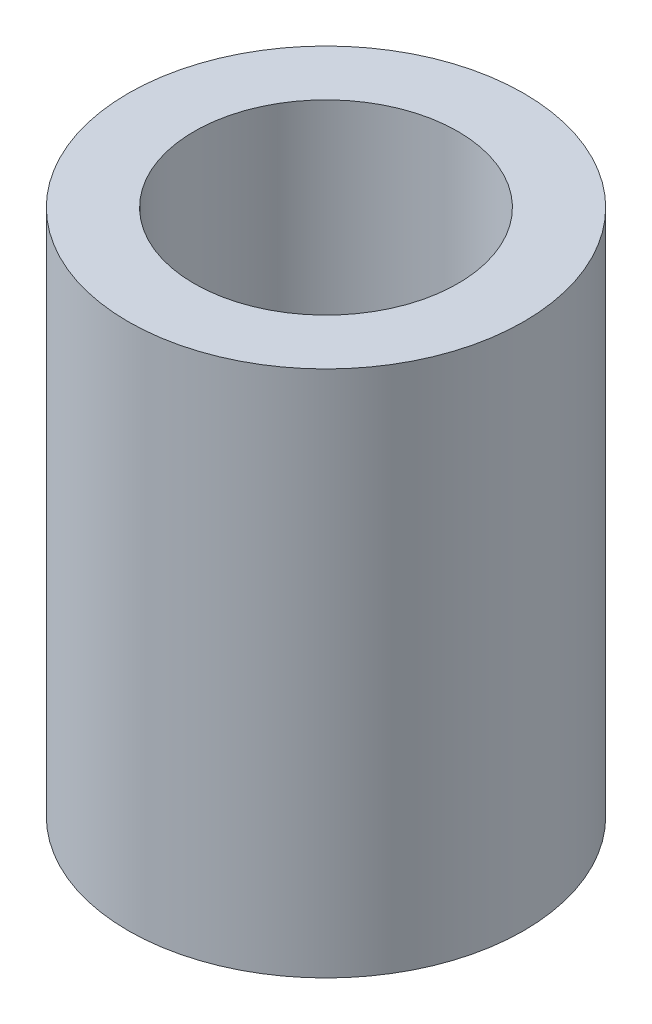
SolidWorks part; units mm, degrees
ref_plane "Front Plane" through (0, 0, 0) normal (0, 0, 1) x (1, 0, 0)
ref_plane "Top Plane" through (0, 0, 0) normal (0, 1, 0) x (1, 0, 0)
ref_plane "Right Plane" through (0, 0, 0) normal (1, 0, 0) x (0, 0, -1)
sketch "Sketch1" plane through (0, 0, 0) normal (0, 1, 0) x (1, 0, 0)
  circle A0 centre (0, 0) radius 2
  circle A1 centre (0, 0) radius 3
extrude "Boss-Extrude1" add sketch "Sketch1" along normal blind 8
